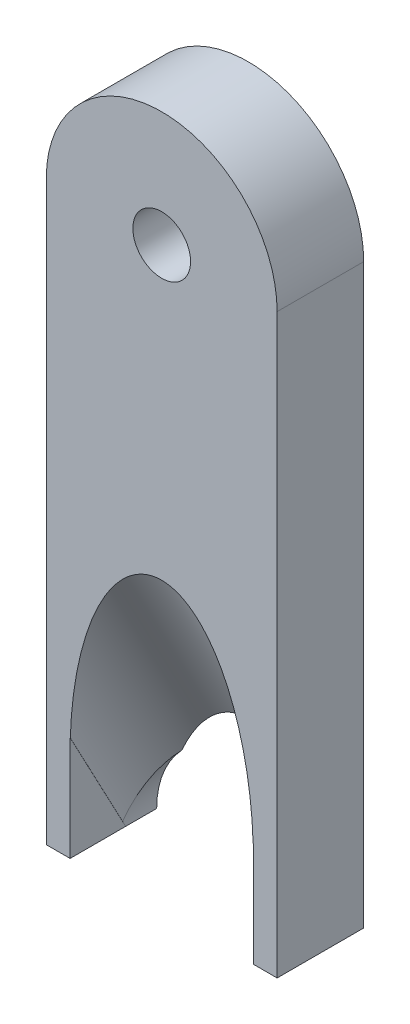
SolidWorks part; units mm, degrees
ref_plane "Front Plane" through (0, 0, 0) normal (0, 0, 1) x (1, 0, 0)
ref_plane "Top Plane" through (0, 0, 0) normal (0, 1, 0) x (1, 0, 0)
ref_plane "Right Plane" through (0, 0, 0) normal (1, 0, 0) x (0, 0, -1)
sketch "Sketch1" plane through (0, 0, 0) normal (0, 0, 1) x (1, 0, 0)
  line L0 (-20, 0) -> (-20, -100)
  line L1 (-20, -100) -> (-15.875, -100)
  line L2 (20, 0) -> (20, -100)
  line L3 (20, -100) -> (15.875, -100)
  circle A0 centre (0, 0) radius 5
  arc A1 (20, 0) -> (-20, 0) centre (0, 0) ccw
  arc A2 (-15.875, -100) -> (15.875, -100) centre (0, -100) cw
  point P3 (0, 0)
  point P11 (0, 0)
  dimension "D1" = 10
  dimension "D2" = 40
  dimension "D3" = 15.875
  dimension "D4" = 100
extrude "Boss-Extrude1" add sketch "Sketch1" along normal blind 15
ref_plane "Plane1" through (0, -77.9596, -41.4519) normal (0, 0.8829, 0.4695) x (1, 0, 0)
sketch "Sketch2" plane through (0, -77.9596, -41.4519) normal (0, 0.8829, 0.4695) x (1, 0, 0)
  line L0 (15.875, -60.1914) -> (15.875, -46.9472) construction
  line L1 (-15.875, -60.1914) -> (-15.875, -46.9472) construction
  circle A0 centre (0, -52.7385) radius 15.875
  ellipse E0 centre (0, -60.1914) end of major axis (15.875, -60.1914) minor radius 7.4529 (15.875, -60.1914) -> (-15.875, -60.1914) ccw construction
  point P11 (0, 0)
  point P12 (0, 0)
extrude "Cut-Extrude1" cut sketch "Sketch2" along normal blind 64
sketch "Sketch4" plane through (0, -77.9596, -41.4519) normal (0, 0.8829, 0.4695) x (1, 0, 0)
  line L0 (-15.875, -52.7385) -> (-15.875, -46.9472) construction
  line L1 (15.875, -60.1914) -> (-15.875, -60.1914)
  line L2 (15.875, -60.1914) -> (15.875, -51.6914)
  line L3 (15.875, -51.6914) -> (-15.875, -51.6914)
  line L4 (-15.875, -60.1914) -> (-15.875, -51.6914)
  dimension "D1" = 8.5
extrude "Cut-Extrude2" cut sketch "Sketch4" along normal blind 61
